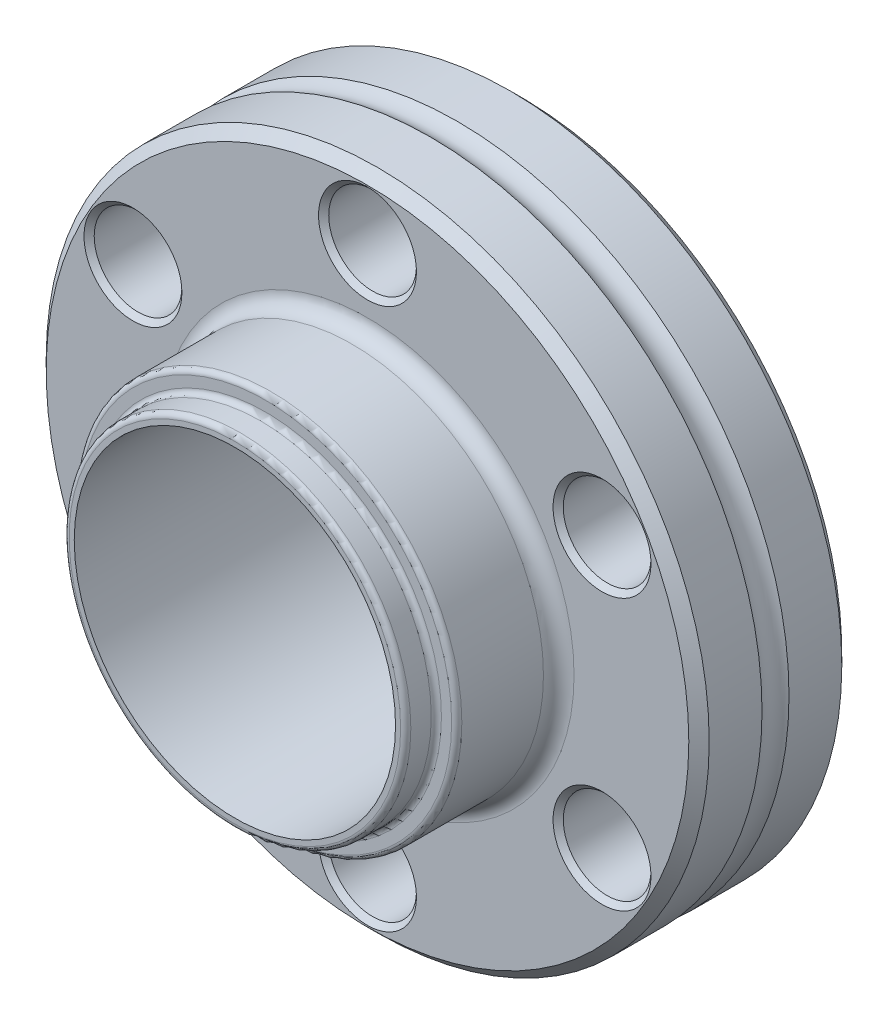
SolidWorks part; units mm, degrees
material "AISI 304"
ref_plane "Front Plane" through (0, 0, 0) normal (0, 0, 1) x (1, 0, 0)
ref_plane "Top Plane" through (0, 0, 0) normal (0, 1, 0) x (1, 0, 0)
ref_plane "Right Plane" through (0, 0, 0) normal (1, 0, 0) x (0, 0, -1)
sketch "Sketch1" plane through (0, 0, 0) normal (0, 1, 0) x (1, 0, 0)
  line L0 (9.0861, 5.9436) -> (0, 5.9436)
  line L1 (0, 5.9436) -> (0, -0.508)
  line L2 (0, -0.508) -> (16.51, -0.508)
  line L3 (16.51, -0.508) -> (16.51, 2.63)
  line L4 (16.51, 3.974) -> (16.51, 7.112)
  line L5 (16.51, 7.112) -> (10.7315, 7.112)
  line L6 (10.7315, 7.112) -> (10.7315, 5.92)
  line L7 (10.7315, 5.92) -> (9.271, 6.4516)
  line L8 (9.271, 6.4516) -> (9.0861, 5.9436)
  line L9 (0, 7.112) -> (0, -0.508) construction
  arc A0 (16.51, 2.63) -> (16.51, 3.974) centre (17.272, 3.302) cw
revolve "Revolve1" add sketch "Sketch1" angle 360 about L9
sketch "Sketch2" plane through (0, 0, 0.508) normal (0, 0, 1) x (1, 0, 0)
  circle A0 centre (0, 0) radius 9.525
extrude "Boss-Extrude1" add sketch "Sketch2" along normal blind 5.08
sketch "Sketch3" plane through (0, 0, 5.588) normal (0, 0, 1) x (1, 0, 0)
  circle A0 centre (0, 0) radius 8.509
extrude "Boss-Extrude2" add sketch "Sketch3" along normal blind 1.524
hole_wizard "Hole1" positions "Sketch5" profile "Sketch4" legacy
sketch "Sketch5" plane through (0, 0, 7.112) normal (0, 0, 1) x (1, 0, 0)
  point P0 (0, 0)
sketch "Sketch4" plane through (0, 0, 7.112) normal (1, 0, 0) x (0, -1, 0)
  line L0 (0, 0) -> (0, 14.224)
  line L1 (0, 14.224) -> (8.001, 14.224)
  line L2 (8.001, 14.224) -> (8.001, 0)
  line L3 (8.001, 0) -> (0, 0)
  line L4 (0, 110) -> (0, -10) construction
  dimension "Diameter" = 16.002
  dimension "Depth" = 14.224
hole_wizard "#8 Clearance Hole1" positions "Sketch7" profile "Sketch6" hole size "#8" standard "ANSI Inch"
sketch "Sketch7" plane through (0, 0, 0.508) normal (0, 0, 1) x (1, 0, 0)
  point P0 (11.6804, -6.7437)
sketch "Sketch6" plane through (11.6804, -6.7437, 0.508) normal (1, 0, 0) x (0, -1, 0)
  line L0 (0, 0) -> (0, 7.62)
  line L1 (0, 7.62) -> (2.1844, 7.62)
  line L2 (2.1844, 7.62) -> (2.1844, 0)
  line L5 (2.1844, 0) -> (0, 0)
  line L11 (0, -6.35) -> (0, 107.95) construction
  dimension "Thru Hole Dia." = 4.3688
  dimension "Thru Hole Depth" = 7.62
hole_wizard "#8 Clearance Hole2" positions "Sketch9" profile "Sketch8" hole size "#8" standard "ANSI Inch"
sketch "Sketch9" plane through (0, 0, -7.112) normal (0, 0, -1) x (-1, 0, 0)
  point P0 (0, 13.4874)
  point P1 (11.6804, 6.7437)
  point P2 (11.6804, -6.7437)
  point P3 (0, -13.4874)
  point P4 (-11.6804, 6.7437)
sketch "Sketch8" plane through (0, 13.4874, -7.112) normal (1, 0, 0) x (0, 1, 0)
  line L0 (0, 0) -> (0, 14.224)
  line L1 (0, 14.224) -> (2.1844, 14.224)
  line L2 (2.1844, 14.224) -> (2.1844, 0)
  line L5 (2.1844, 0) -> (0, 0)
  line L11 (0, -6.35) -> (0, 107.95) construction
  dimension "Thru Hole Dia." = 4.3688
  dimension "Thru Hole Depth" = 14.224
chamfer "Chamfer1" distance 0.254 angle 45 12 edges at (13.8648, -6.7437, -7.112) (2.1844, -13.4874, 0.508) (-9.496, 6.7437, 0.508) (13.8648, 6.7437, 0.508) (-2.1844, -13.4874, -7.112) (9.496, 6.7437, -7.112) (2.1844, 13.4874, 0.508) (-9.496, -6.7437, 0.508) (13.8648, -6.7437, 0.508) (-13.8648, -6.7437, -7.112) (-2.1844, 13.4874, -7.112) (-13.8648, 6.7437, -7.112)
chamfer "Chamfer2" distance 0.508 angle 45 2 edges at (16.51, 0, -7.112) (16.51, 0, 0.508)
fillet "Fillet1" radius 0.254 4 edges at (9.525, 0, 5.588) (8.509, 0, 5.588) (8.509, 0, 7.112) (-8.001, 0, -5.9436)
fillet "Fillet2" radius 0.762 1 edges at (9.525, 0, 0.508)
